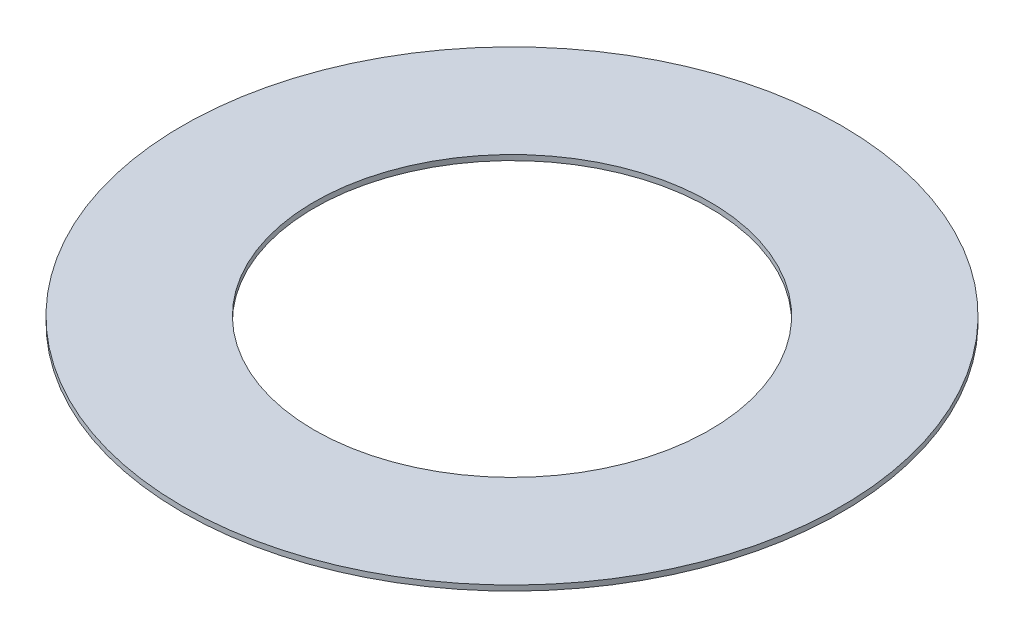
SolidWorks part; units mm, degrees
material "Plain Carbon Steel"
ref_plane "Front Plane" through (0, 0, 0) normal (0, 0, 1) x (1, 0, 0)
ref_plane "Top Plane" through (0, 0, 0) normal (0, 1, 0) x (1, 0, 0)
ref_plane "Right Plane" through (0, 0, 0) normal (1, 0, 0) x (0, 0, -1)
sketch "Sketch1" plane through (0, 0, 0) normal (0, 1, 0) x (1, 0, 0)
  circle A0 centre (0, 0) radius 7.9375
  dimension "OD" = 15.875
extrude "Boss-Extrude1" add sketch "Sketch1" along normal blind 0.127
sketch "Sketch5" plane through (0, 0.127, 0) normal (0, 1, 0) x (-1, 0, 0)
  circle A0 centre (0, 0) radius 4.7625
  dimension "ID" = 9.525
extrude "Cut-Extrude1" cut sketch "Sketch5" against normal through all
